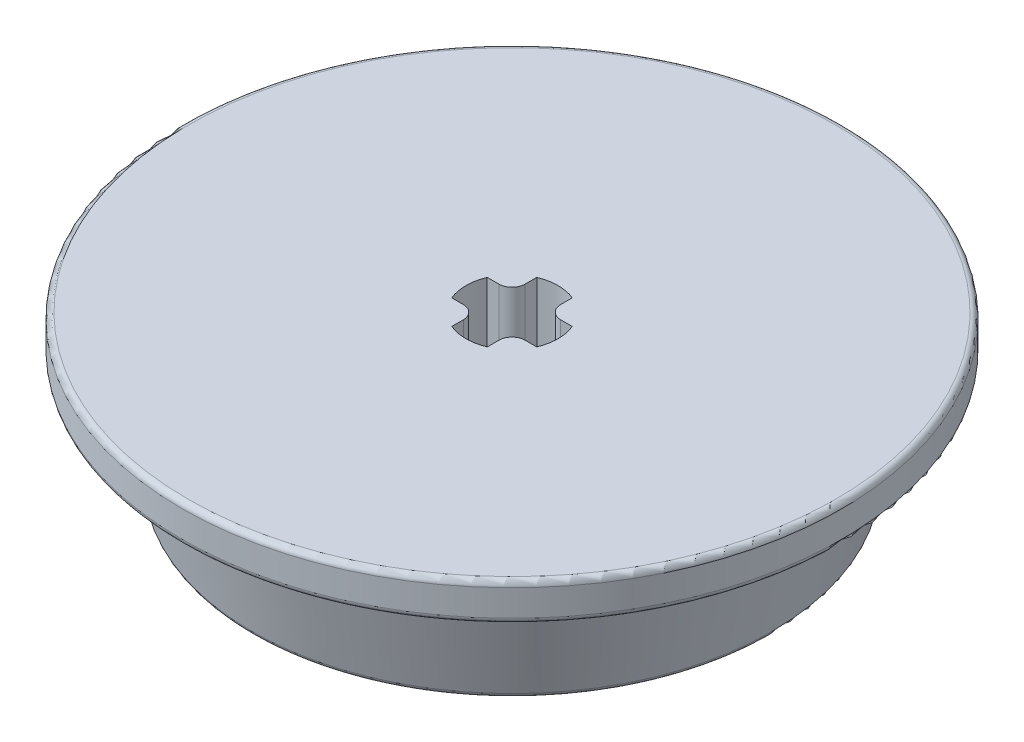
SolidWorks part; units mm, degrees
ref_plane "Front Plane" through (0, 0, 0) normal (0, 0, 1) x (1, 0, 0)
ref_plane "Top Plane" through (0, 0, 0) normal (0, 1, 0) x (1, 0, 0)
ref_plane "Right Plane" through (0, 0, 0) normal (1, 0, 0) x (0, 0, -1)
sketch "Sketch1" plane through (0, 0, 0) normal (0, 1, 0) x (1, 0, 0)
  line L2 (0, 0) -> (0, 47.5777) construction
  line L3 (0, 0) -> (50000, 0) construction
  line L6 (-0.89, 0.89) -> (0, 0) construction
  line L7 (0, 0) -> (0.89, 0.89) construction
  line L12 (2.39, 0) -> (2.39, 3.5727) construction
  line L13 (0, 2.39) -> (50000, 2.39) construction
  line L14 (-2.39, 0.4111) -> (-2.39, -49999.5889) construction
  line L15 (0.2318, -2.39) -> (-49999.7682, -2.39) construction
  line L16 (0, 0) -> (-0.89, -0.89) construction
  line L17 (0, 0) -> (0.89, -0.89) construction
  line L18 (-0.94, 0.94) -> (-2.2517, 0.94)
  line L19 (-2.2517, -0.94) -> (-0.94, -0.94)
  line L20 (-0.94, -0.94) -> (-0.94, -2.2517)
  line L21 (0.94, -2.2517) -> (0.94, -0.94)
  line L22 (0.94, -0.94) -> (2.2517, -0.94)
  line L23 (0.94, 0.94) -> (2.2517, 0.94)
  line L24 (0.94, 2.2517) -> (0.94, 0.94)
  line L25 (-0.94, 2.2517) -> (-0.94, 0.94)
  arc A4 (-2.2517, 0.94) -> (-2.2517, -0.94) centre (0, 0) ccw
  arc A5 (-0.94, -2.2517) -> (0.94, -2.2517) centre (0, 0) ccw
  arc A6 (2.2517, 0.94) -> (2.2517, -0.94) centre (0, 0) cw
  arc A7 (-0.94, 2.2517) -> (0.94, 2.2517) centre (0, 0) cw
  point P15 (0, 2.39)
  point P24 (2.39, 0)
  point P29 (-2.39, 0)
  point P30 (0, -2.39)
  line B0 (-0.89, 2.2181) -> (-0.89, 0.89) construction
  line B1 (-0.89, 0.89) -> (-2.2181, 0.89) construction
  line B2 (0.89, 2.2181) -> (0.89, 0.89) construction
  line B3 (0.89, 0.89) -> (2.2181, 0.89) construction
  line B4 (-2.2181, -0.89) -> (-0.89, -0.89) construction
  line B5 (-0.89, -0.89) -> (-0.89, -2.2181) construction
  line B6 (0.89, -2.2181) -> (0.89, -0.89) construction
  line B7 (0.89, -0.89) -> (2.2181, -0.89) construction
  arc B8 (-0.89, 2.2181) -> (0.89, 2.2181) centre (0, 0) cw construction
  arc B9 (-2.2181, 0.89) -> (-2.2181, -0.89) centre (0, 0) ccw construction
  arc B10 (2.2181, 0.89) -> (2.2181, -0.89) centre (0, 0) cw construction
  arc B11 (-0.89, -2.2181) -> (0.89, -2.2181) centre (0, 0) ccw construction
sketch_block_instance "Lego Axle - Unfilleted-1"
sketch_block "Lego Axle - Unfilleted" parameters "D1"=10.5762, "D2"=12.3972, "D3"=62.5785, "D4"=1.2287, "D5"=12.9019, "D6"=1.0841, "D7"=0.05
sketch "Sketch2" plane through (0, 0, 0) normal (0, 0, 1) x (1, 0, 0)
  line L0 (0, 0) -> (17.4605, 0)
  line L1 (200000.2318, 0) -> (-249999.7682, 0) construction
  line L2 (17.4605, 0) -> (17.4605, -2)
  line L3 (17.4605, -2) -> (15, -2)
  line L4 (15, -2) -> (13.7247, -8)
  line L5 (13.7247, -8) -> (0, -8)
  line L6 (0, -8) -> (0, 0)
  line L7 (0, 0) -> (0, 50000) construction
  dimension "D1" = 30
  dimension "D2" = 12
  dimension "D3" = 8
  dimension "D4" = 2
revolve "Revolve1" add sketch "Sketch2" angle 360 about L7
extrude "Cut-Extrude1" cut sketch "Sketch1" against normal through all
fillet "Fillet1" radius 0.7 4 edges at (-0.94, -4, 0.94) (0.94, -4, 0.94) (0.94, -4, -0.94) (-0.94, -4, -0.94)
fillet "Fillet2" radius 0.3 4 edges at (0, -8, -13.7247) (0, 0, -17.4605) (0, -2, -15) (0, -2, -17.4605)
